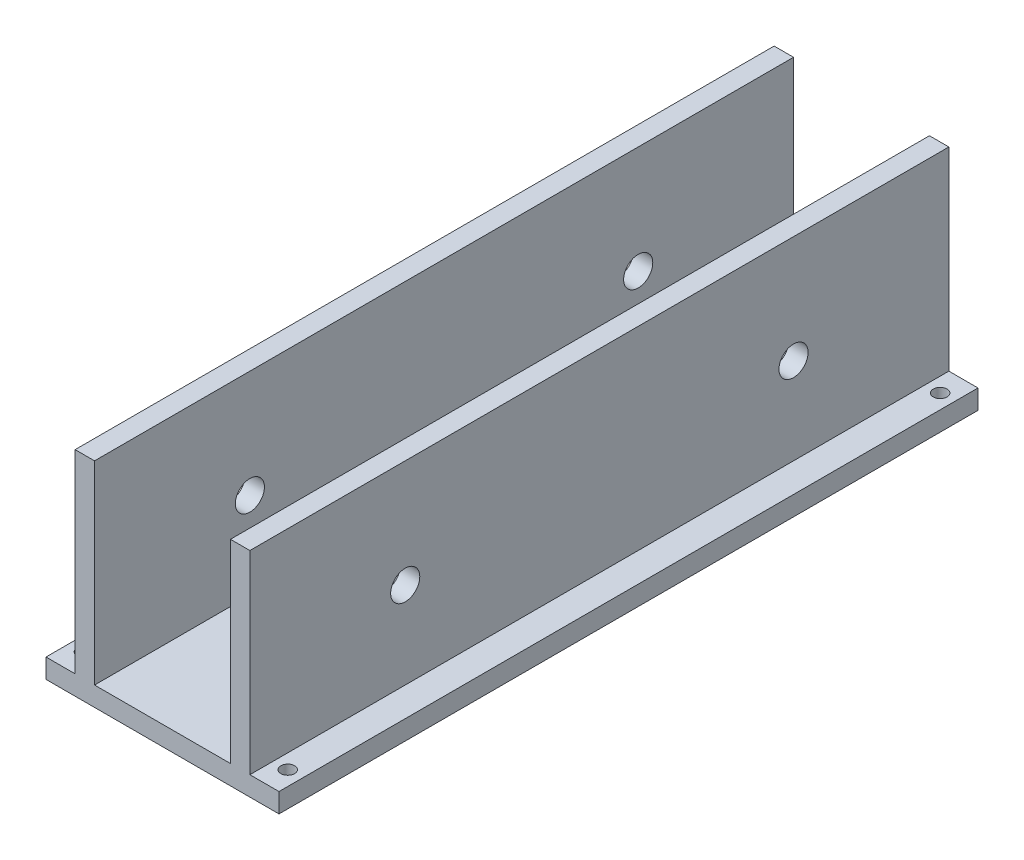
SolidWorks part; units mm, degrees
ref_plane "Front Plane" through (0, 0, 0) normal (0, 0, 1) x (1, 0, 0)
ref_plane "Top Plane" through (0, 0, 0) normal (0, 1, 0) x (1, 0, 0)
ref_plane "Right Plane" through (0, 0, 0) normal (1, 0, 0) x (0, 0, -1)
sketch "Sketch1" plane through (0, 0, 0) normal (0, 0, 1) x (1, 0, 0)
  line L0 (0, 0) -> (76.2, 0)
  line L1 (23.0864, 0) -> (-23.0864, 0) construction
  line L2 (76.2, 0) -> (76.2, 6.35)
  line L3 (76.2, 6.35) -> (66.675, 6.35)
  line L4 (66.675, 6.35) -> (66.675, 69.85)
  line L5 (66.675, 69.85) -> (60.325, 69.85)
  line L6 (60.325, 69.85) -> (60.325, 6.35)
  line L7 (60.325, 6.35) -> (15.875, 6.35)
  line L8 (15.875, 6.35) -> (15.875, 69.85)
  line L9 (15.875, 69.85) -> (9.525, 69.85)
  line L10 (9.525, 69.85) -> (9.525, 6.35)
  line L11 (9.525, 6.35) -> (0, 6.35)
  line L12 (0, -22.8874) -> (0, 22.8874) construction
  line L13 (0, 6.35) -> (0, 0)
  dimension "D1" = 76.2
  dimension "D2" = 6.35
  dimension "D3" = 44.45
  dimension "D4" = 6.35
  dimension "D5" = 69.85
extrude "Boss-Extrude1" add sketch "Sketch1" along normal blind 228.6
sketch "Sketch4" plane through (0, 6.35, 0) normal (0, 1, 0) x (1, 0, 0)
  line L0 (9.525, -1.9805) -> (0, -1.9805) construction
  line L1 (9.525, -228.6) -> (9.525, 0) construction
  line L2 (0, -55) -> (0, 55) construction
  line L3 (4.7625, -1.9805) -> (4.7625, -234.5838) construction
  line L4 (9.525, -228.6) -> (0, -228.6) construction
  line L5 (-55, 0) -> (55, 0) construction
  line L6 (38.1, -228.6) -> (38.1, 78.8755) construction
  line L7 (60.325, -228.6) -> (15.875, -228.6) construction
  circle A0 centre (4.7625, -7.62) radius 2.2479
  circle A1 centre (4.7625, -220.98) radius 2.2479
  circle A2 centre (71.4375, -220.98) radius 2.2479
  circle A3 centre (71.4375, -7.62) radius 2.2479
  dimension "D1" = 4.4958
  dimension "D3" = 4.4958
  dimension "D2" = 7.62
  dimension "D4" = 7.62
extrude "Cut-Extrude1" cut sketch "Sketch4" against normal through all
sketch "Sketch5" plane through (66.675, 0, 0) normal (1, 0, 0) x (0, 0, -1)
  line L0 (-228.6, 6.35) -> (-228.6, 69.85) construction
  circle A0 centre (-177.8, 34.6769) radius 4.7625
  circle A1 centre (-50.8, 34.6769) radius 4.7625
  dimension "D1" = 9.525
  dimension "D2" = 127
  dimension "D3" = 50.8
extrude "Cut-Extrude2" cut sketch "Sketch5" against normal through all
